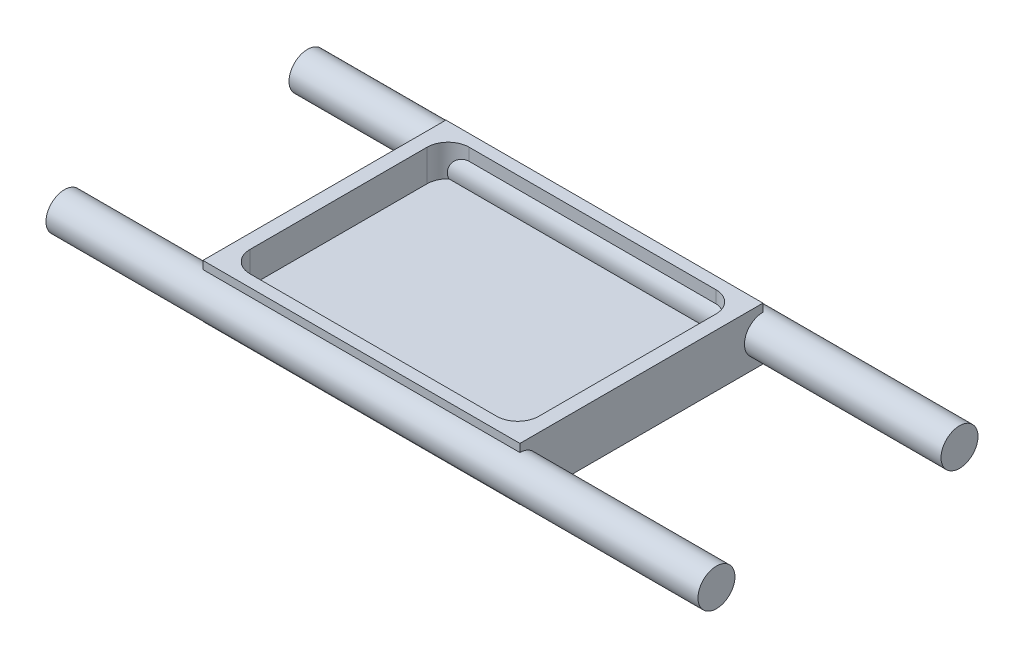
SolidWorks part; units mm, degrees
ref_plane "Front Plane" through (0, 0, 0) normal (0, 0, 1) x (1, 0, 0)
ref_plane "Top Plane" through (0, 0, 0) normal (0, 1, 0) x (1, 0, 0)
ref_plane "Right Plane" through (0, 0, 0) normal (1, 0, 0) x (0, 0, -1)
sketch "Sketch1" plane through (0, 0, 0) normal (0, 1, 0) x (1, 0, 0)
  line L1 (150, 115) -> (-150, 115)
  line L2 (150, 115) -> (150, -115)
  line L3 (150, -115) -> (-150, -115)
  line L4 (-150, 115) -> (-150, -115)
  line L5 (150, 115) -> (-150, -115) construction
  line L6 (150, -115) -> (-150, 115) construction
  point P0 (0, 0)
  dimension "D1" = 230
  dimension "D2" = 300
extrude "Boss-Extrude1" add sketch "Sketch1" along normal blind 50
sketch "Sketch2" plane through (0, 50, 0) normal (0, 1, 0) x (1, 0, 0)
  line L1 (116.7022, 103.7472) -> (-116.7022, 103.7472)
  line L2 (136.7022, 83.7472) -> (136.7022, -83.7472)
  line L3 (116.7022, -103.7472) -> (-116.7022, -103.7472)
  line L4 (-136.7022, 83.7472) -> (-136.7022, -83.7472)
  line L5 (136.7022, 103.7472) -> (-136.7022, -103.7472) construction
  line L6 (136.7022, -103.7472) -> (-136.7022, 103.7472) construction
  arc A0 (116.7022, -103.7472) -> (136.7022, -83.7472) centre (116.7022, -83.7472) ccw
  arc A1 (116.7022, 103.7472) -> (136.7022, 83.7472) centre (116.7022, 83.7472) cw
  arc A2 (-116.7022, 103.7472) -> (-136.7022, 83.7472) centre (-116.7022, 83.7472) ccw
  arc A3 (-136.7022, -83.7472) -> (-116.7022, -103.7472) centre (-116.7022, -83.7472) ccw
  point P0 (0, 0)
  dimension "D1" = 20
extrude "Cut-Extrude1" cut sketch "Sketch2" against normal blind 30
sketch "Sketch3" plane through (150, 0, 0) normal (1, 0, 0) x (0, 0, -1)
  line L0 (115, 50) -> (115, 0) construction
  line L1 (-115, 50) -> (-115, 0) construction
  circle A0 centre (115, 25) radius 17.5
  circle A1 centre (-115, 25) radius 17.5
  dimension "D1" = 35
  dimension "D2" = 35
extrude "Boss-Extrude2" add sketch "Sketch3" against normal blind 431 and the other way blind 186
